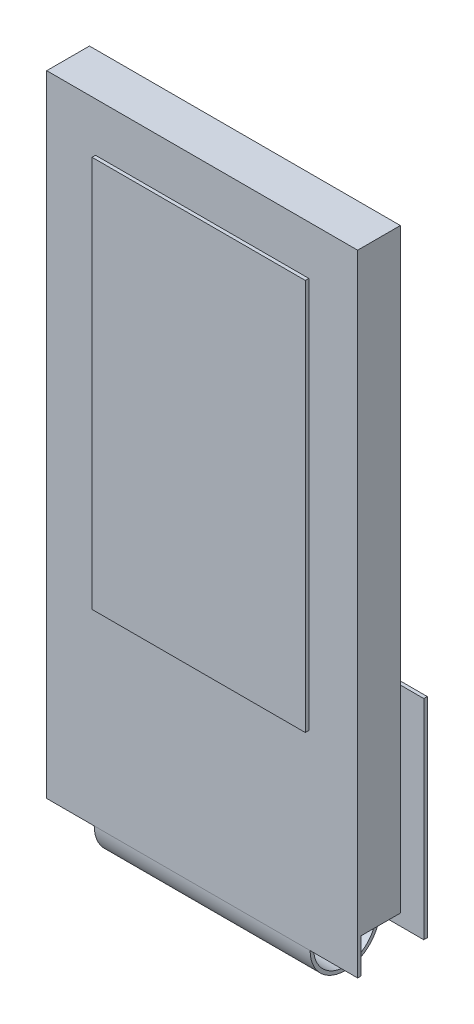
SolidWorks part; units mm, degrees
ref_plane "Plan de face" through (0, 0, 0) normal (0, 0, 1) x (1, 0, 0)
ref_plane "Plan de dessus" through (0, 0, 0) normal (0, 1, 0) x (1, 0, 0)
ref_plane "Plan de droite" through (0, 0, 0) normal (1, 0, 0) x (0, 0, -1)
sketch "Esquisse1" plane through (0, 0, 0) normal (0, 0, 1) x (1, 0, 0)
  line L1 (-4.464, -8.55) -> (4.464, -8.55)
  line L2 (-4.464, -8.55) -> (-4.464, 8.55)
  line L3 (-4.464, 8.55) -> (4.464, 8.55)
  line L4 (4.464, -8.55) -> (4.464, 8.55)
  line L5 (-4.464, -8.55) -> (4.464, 8.55) construction
  line L6 (-4.464, 8.55) -> (4.464, -8.55) construction
  point P0 (0, 0)
  dimension "D1" = 8.928
  dimension "D2" = 17.1
extrude "Boss.-Extru.1" add sketch "Esquisse1" along normal blind 1.227
sketch "Esquisse2" plane through (0, 0, 1.227) normal (0, 0, 1) x (1, 0, 0)
  line L0 (-4.464, -5.5) -> (4.464, -5.5) construction
  line L1 (-4.464, 8.55) -> (-4.464, -8.55) construction
  line L2 (4.464, -8.55) -> (4.464, 8.55) construction
  line L3 (4.464, 8.55) -> (-4.464, 8.55) construction
  line L4 (-4.464, 8.55) -> (4.464, -5.5) construction
  line L6 (-3.062, -4.097) -> (3.062, -4.097)
  line L7 (-3.062, -4.097) -> (-3.062, 7.147)
  line L8 (-3.062, 7.147) -> (3.062, 7.147)
  line L9 (3.062, -4.097) -> (3.062, 7.147)
  line L10 (-3.062, -4.097) -> (3.062, 7.147) construction
  line L11 (-3.062, 7.147) -> (3.062, -4.097) construction
  point P9 (0, 1.525)
  dimension "D1" = 14.05
  dimension "D2" = 6.124
  dimension "D3" = 11.244
extrude "Boss.-Extru.2" add sketch "Esquisse2" along normal blind 0.1
ref_plane "Plan1" through (0, 1.525, 0) normal (0, -1, 0) x (-1, 0, 0)
ref_plane "Plan2" through (0, 0, 0) normal (-1, 0, 0) x (0, 1, 0)
sketch "Esquisse4" plane through (4.464, 0, 0) normal (1, 0, 0) x (0, 0, -1)
  line L0 (-1.227, -8.55) -> (-1.227, -9.55)
  line L1 (0.773, -9.55) -> (0.773, -3.55)
  line L2 (0.773, -3.55) -> (0.673, -3.55)
  line L3 (0.673, -3.55) -> (0.673, -9.55)
  line L4 (-1.127, -9.55) -> (-1.127, -8.55)
  line L5 (-1.227, -8.55) -> (0, -8.55) construction
  line L6 (-1.127, -8.55) -> (-1.227, -8.55)
  arc A0 (-1.227, -9.55) -> (0.773, -9.55) centre (-0.227, -9.55) ccw
  arc A1 (0.673, -9.55) -> (-1.127, -9.55) centre (-0.227, -9.55) cw
  dimension "D2" = 1
  dimension "D4" = 1
  dimension "D1" = 0.1
  dimension "D3" = 6
extrude "Boss.-Extru.4" add sketch "Esquisse4" against normal up to surface (8.928 mm away) up to face at (-4.464, 0, 0.6135)
sketch "Esquisse5" plane through (0, 0, 1.227) normal (0, 0, 1) x (1, 0, 0)
  line L1 (-4.464, -9.55) -> (4.464, -9.55) construction
  line L2 (3.1, -9.55) -> (3.1, -10.55)
  line L3 (-4.464, -10.55) -> (4.464, -10.55) construction
  line L5 (-3.1, -10.55) -> (-3.1, -9.55)
  line L6 (3.1, -10.55) -> (4.464, -10.55)
  line L7 (-4.464, -10.55) -> (-3.1, -10.55)
  line L8 (-4.464, -10.55) -> (-4.464, -9.55)
  line L9 (-4.464, -9.55) -> (-3.1, -9.55)
  line L10 (4.464, -10.55) -> (4.464, -9.55)
  line L11 (3.1, -9.55) -> (4.464, -9.55)
  line L12 (3.1, -9.55) -> (-3.1, -9.55) construction
  line L13 (0, -9.55) -> (0, -10.55) construction
  point P8 (0, -9.55)
  dimension "D1" = 6.2
extrude "Enlèv. mat.-Extru.1" cut sketch "Esquisse5" against normal up to next
